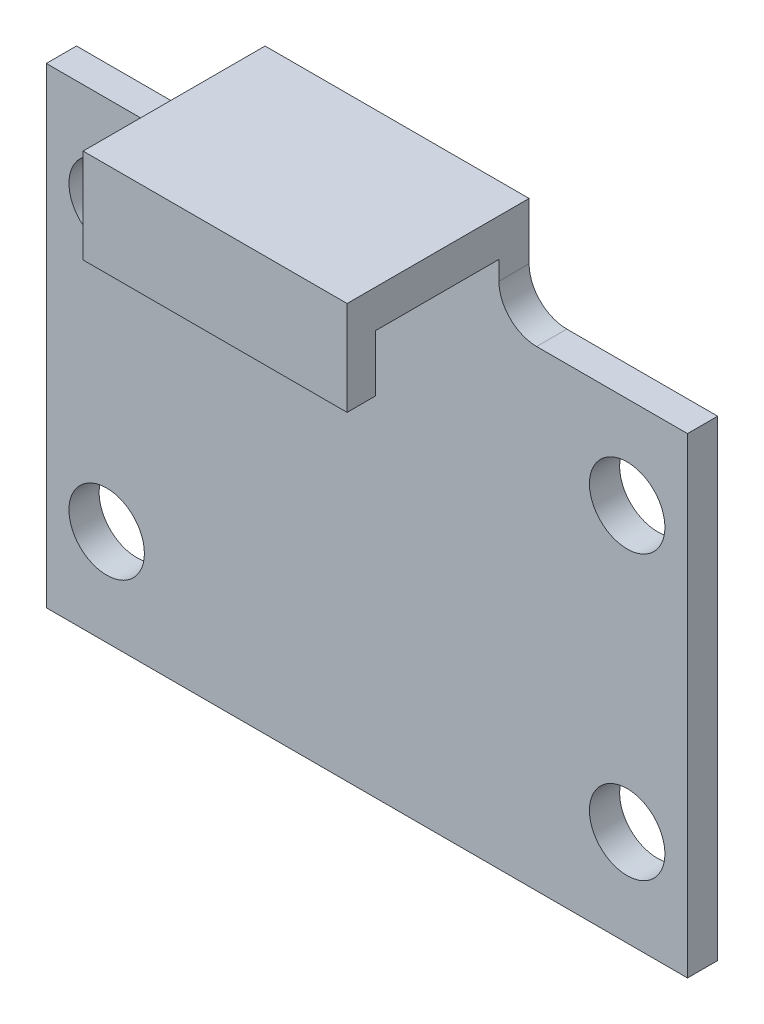
SolidWorks part; units mm, degrees
ref_plane "Front Plane" through (0, 0, 0) normal (0, 0, 1) x (1, 0, 0)
ref_plane "Top Plane" through (0, 0, 0) normal (0, 1, 0) x (1, 0, 0)
ref_plane "Right Plane" through (0, 0, 0) normal (1, 0, 0) x (0, 0, -1)
sketch "Sketch1" plane through (0, 0, 0) normal (0, 0, 1) x (1, 0, 0)
  line L1 (-21.59, 25.4) -> (21.59, 25.4)
  line L2 (-21.59, 25.4) -> (-21.59, -25.4)
  line L3 (-21.59, -25.4) -> (21.59, -25.4)
  line L4 (21.59, 25.4) -> (21.59, -25.4)
  line L5 (-21.59, 25.4) -> (21.59, -25.4) construction
  line L6 (-21.59, -25.4) -> (21.59, 25.4) construction
  point P0 (0, 0)
  dimension "D1" = 43.18
  dimension "D2" = 50.8
extrude "Boss-Extrude1" add sketch "Sketch1" along normal blind 2.032
sketch "Sketch2" plane through (0, 0, 2.032) normal (0, 0, 1) x (1, 0, 0)
  line L0 (21.59, 25.4) -> (-21.59, 25.4) construction
  line L1 (0, 25.4) -> (0, -25.4) construction
  line L2 (-21.59, -25.4) -> (21.59, -25.4) construction
  circle A0 centre (-17.526, 12.827) radius 2.54
  circle A1 centre (-17.526, -6.223) radius 2.54
  circle A2 centre (17.526, -6.223) radius 2.54
  circle A3 centre (17.526, 12.827) radius 2.54
  point P15 (0, 0)
  dimension "D4" = 5.08
  dimension "D5" = 5.08
  dimension "D1" = 17.526
  dimension "D2" = 19.05
  dimension "D3" = 12.573
extrude "Cut-Extrude1" cut sketch "Sketch2" against normal through all
sketch "Sketch3" plane through (0, 0, 2.032) normal (0, 0, 1) x (1, 0, 0)
  line L0 (21.59, -25.4) -> (21.59, 25.4) construction
  line L1 (-21.59, 25.4) -> (21.59, 25.4)
  line L2 (-21.59, 25.4) -> (-21.59, 22.86)
  line L3 (-21.59, 22.86) -> (21.59, 22.86)
  line L4 (21.59, 25.4) -> (21.59, 22.86)
  dimension "D1" = 2.54
extrude "Boss-Extrude2" add sketch "Sketch3" along normal blind 8.3185
sketch "Sketch4" plane through (0, 0, 10.3505) normal (0, 0, 1) x (1, 0, 0)
  line L0 (21.59, 22.86) -> (21.59, 25.4) construction
  line L1 (-21.59, 25.4) -> (21.59, 25.4)
  line L2 (-21.59, 25.4) -> (-21.59, 19.05)
  line L3 (-21.59, 19.05) -> (21.59, 19.05)
  line L4 (21.59, 25.4) -> (21.59, 19.05)
  dimension "D1" = 6.35
extrude "Boss-Extrude3" add sketch "Sketch4" along normal blind 1.905
sketch "Sketch5" plane through (21.59, 0, 0) normal (1, 0, 0) x (0, 0, -1)
  line L1 (0, 25.4) -> (-12.2555, 25.4)
  line L2 (0, 25.4) -> (0, 19.05)
  line L3 (0, 19.05) -> (-12.2555, 19.05)
  line L4 (-12.2555, 25.4) -> (-12.2555, 19.05)
extrude "Cut-Extrude2" cut sketch "Sketch5" against normal blind 12.7
sketch "Sketch6" plane through (-21.59, 0, 0) normal (-1, 0, 0) x (0, 0, 1)
  line L1 (0, 25.4) -> (12.2555, 25.4)
  line L2 (0, 25.4) -> (0, 19.05)
  line L3 (0, 19.05) -> (12.2555, 19.05)
  line L4 (12.2555, 25.4) -> (12.2555, 19.05)
extrude "Cut-Extrude3" cut sketch "Sketch6" against normal blind 12.7
fillet "Fillet1" radius 2.54 2 edges at (8.89, 19.05, 1.016) (-8.89, 19.05, 1.016)
sketch "Sketch7" plane through (0, 0, 2.032) normal (0, 0, 1) x (1, 0, 0)
  line L0 (21.59, -25.4) -> (21.59, 19.05) construction
  line L1 (-21.59, -25.4) -> (21.59, -25.4)
  line L2 (-21.59, -25.4) -> (-21.59, -12.7)
  line L3 (-21.59, -12.7) -> (21.59, -12.7)
  line L4 (21.59, -25.4) -> (21.59, -12.7)
  dimension "D1" = 12.7
extrude "Cut-Extrude4" cut sketch "Sketch7" against normal blind 12.7
